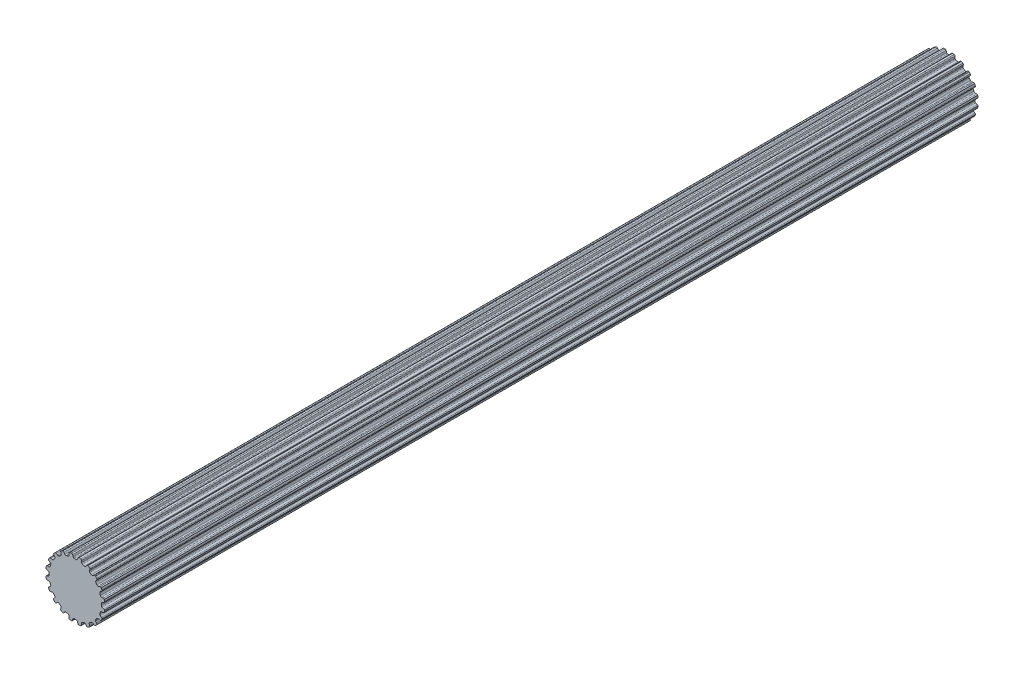
SolidWorks part; units mm, degrees
ref_plane "Front Plane" through (0, 0, 0) normal (0, 0, 1) x (1, 0, 0)
ref_plane "Top Plane" through (0, 0, 0) normal (0, 1, 0) x (1, 0, 0)
ref_plane "Right Plane" through (0, 0, 0) normal (1, 0, 0) x (0, 0, -1)
sketch "Sketch1" plane through (0, 0, 0) normal (0, 0, 1) x (1, 0, 0)
  line L0 (-0.1069, 2.9699) -> (0.1069, 2.9699)
  line L1 (0.3159, 3.2375) -> (0.2537, 3.0575)
  line L2 (-0.2964, 3.2367) -> (-0.2318, 3.0575)
  line L3 (-0.2964, 3.2367) -> (0.3159, 3.2375) construction
  line L4 (0, 3.3252) -> (0, 0) construction
  line L5 (-0.2318, 3.0575) -> (0.2537, 3.0575) construction
  line L6 (-0.4281, 3.3241) -> (0.4281, 3.3263) construction
  line L7 (0.7183, 3.1698) -> (0.7244, 2.9795)
  line L8 (0.816, 2.8576) -> (1.0195, 2.7915)
  line L9 (1.3009, 2.9815) -> (1.1862, 2.8295)
  line L10 (1.6627, 2.7927) -> (1.6097, 2.6099)
  line L11 (1.6591, 2.4655) -> (1.8322, 2.3398)
  line L12 (2.1585, 2.4335) -> (2.0025, 2.3245)
  line L13 (2.4443, 2.1423) -> (2.3374, 1.9847)
  line L14 (2.3398, 1.8322) -> (2.4655, 1.6591)
  line L15 (2.8049, 1.6474) -> (2.6228, 1.5919)
  line L16 (2.9866, 1.2821) -> (2.8363, 1.1653)
  line L17 (2.7915, 1.0195) -> (2.8576, 0.816)
  line L18 (3.1767, 0.7) -> (2.9863, 0.7035)
  line L19 (3.2367, 0.2964) -> (3.0575, 0.2318)
  line L20 (2.9699, 0.1069) -> (2.9699, -0.1069)
  line L21 (3.2375, -0.3159) -> (3.0575, -0.2537)
  line L22 (3.1698, -0.7183) -> (2.9795, -0.7244)
  line L23 (2.8576, -0.816) -> (2.7915, -1.0195)
  line L24 (2.9815, -1.3009) -> (2.8295, -1.1862)
  line L25 (2.7927, -1.6627) -> (2.6099, -1.6097)
  line L26 (2.4655, -1.6591) -> (2.3398, -1.8322)
  line L27 (2.4335, -2.1585) -> (2.3245, -2.0025)
  line L28 (2.1423, -2.4443) -> (1.9847, -2.3374)
  line L29 (1.8322, -2.3398) -> (1.6591, -2.4655)
  line L30 (1.6474, -2.8049) -> (1.5919, -2.6228)
  line L31 (1.2821, -2.9866) -> (1.1653, -2.8363)
  line L32 (1.0195, -2.7915) -> (0.816, -2.8576)
  line L33 (0.7, -3.1767) -> (0.7035, -2.9863)
  line L34 (0.2964, -3.2367) -> (0.2318, -3.0575)
  line L35 (0.1069, -2.9699) -> (-0.1069, -2.9699)
  line L36 (-0.3159, -3.2375) -> (-0.2537, -3.0575)
  line L37 (-0.7183, -3.1698) -> (-0.7244, -2.9795)
  line L38 (-0.816, -2.8576) -> (-1.0195, -2.7915)
  line L39 (-1.3009, -2.9815) -> (-1.1862, -2.8295)
  line L40 (-1.6627, -2.7927) -> (-1.6097, -2.6099)
  line L41 (-1.6591, -2.4655) -> (-1.8322, -2.3398)
  line L42 (-2.1585, -2.4335) -> (-2.0025, -2.3245)
  line L43 (-2.4443, -2.1423) -> (-2.3374, -1.9847)
  line L44 (-2.3398, -1.8322) -> (-2.4655, -1.6591)
  line L45 (-2.8049, -1.6474) -> (-2.6228, -1.5919)
  line L46 (-2.9866, -1.2821) -> (-2.8363, -1.1653)
  line L47 (-2.7915, -1.0195) -> (-2.8576, -0.816)
  line L48 (-3.1767, -0.7) -> (-2.9863, -0.7035)
  line L49 (-3.2367, -0.2964) -> (-3.0575, -0.2318)
  line L50 (-2.9699, -0.1069) -> (-2.9699, 0.1069)
  line L51 (-3.2375, 0.3159) -> (-3.0575, 0.2537)
  line L52 (-3.1698, 0.7183) -> (-2.9795, 0.7244)
  line L53 (-2.8576, 0.816) -> (-2.7915, 1.0195)
  line L54 (-2.9815, 1.3009) -> (-2.8295, 1.1862)
  line L55 (-2.7927, 1.6627) -> (-2.6099, 1.6097)
  line L56 (-2.4655, 1.6591) -> (-2.3398, 1.8322)
  line L57 (-2.4335, 2.1585) -> (-2.3245, 2.0025)
  line L58 (-2.1423, 2.4443) -> (-1.9847, 2.3374)
  line L59 (-1.8322, 2.3398) -> (-1.6591, 2.4655)
  line L60 (-1.6474, 2.8049) -> (-1.5919, 2.6228)
  line L61 (-1.2821, 2.9866) -> (-1.1653, 2.8363)
  line L62 (-1.0195, 2.7915) -> (-0.816, 2.8576)
  line L63 (-0.7, 3.1767) -> (-0.7035, 2.9863)
  line L64 (0.4281, 3.3263) -> (0.62, 3.2938)
  line L65 (1.4351, 3.0312) -> (1.6075, 2.9409)
  line L66 (2.3015, 2.4394) -> (2.4376, 2.3003)
  line L67 (2.9427, 1.6088) -> (3.0291, 1.4344)
  line L68 (3.2958, 0.6207) -> (3.3241, 0.4281)
  line L69 (3.3263, -0.4281) -> (3.2938, -0.62)
  line L70 (3.0312, -1.4351) -> (2.9409, -1.6075)
  line L71 (2.4394, -2.3015) -> (2.3003, -2.4376)
  line L72 (1.6088, -2.9427) -> (1.4344, -3.0291)
  line L73 (0.6207, -3.2958) -> (0.4281, -3.3241)
  line L74 (-0.4281, -3.3263) -> (-0.62, -3.2938)
  line L75 (-1.4351, -3.0312) -> (-1.6075, -2.9409)
  line L76 (-2.3015, -2.4394) -> (-2.4376, -2.3003)
  line L77 (-2.9427, -1.6088) -> (-3.0291, -1.4344)
  line L78 (-3.2958, -0.6207) -> (-3.3241, -0.4281)
  line L79 (-3.3263, 0.4281) -> (-3.2938, 0.62)
  line L80 (-3.0312, 1.4351) -> (-2.9409, 1.6075)
  line L81 (-2.4394, 2.3015) -> (-2.3003, 2.4376)
  line L82 (-1.6088, 2.9427) -> (-1.4344, 3.0291)
  line L83 (-0.6207, 3.2958) -> (-0.4281, 3.3241)
  arc A0 (0.2537, 3.0575) -> (0.1069, 2.9699) centre (0.1283, 3.1009) cw
  arc A1 (-0.2318, 3.0575) -> (-0.1069, 2.9699) centre (-0.1069, 3.1026) ccw
  arc A2 (0.62, 3.2938) -> (0.7183, 3.1698) centre (0.5856, 3.1656) cw
  arc A3 (0.7244, 2.9795) -> (0.816, 2.8576) centre (0.857, 2.9838) ccw
  arc A4 (-0.4281, 3.3241) -> (-0.2964, 3.2367) centre (-0.4213, 3.1916) cw
  arc A5 (0.4281, 3.3263) -> (0.3159, 3.2375) centre (0.4413, 3.1942) ccw
  arc A6 (1.1862, 2.8295) -> (1.0195, 2.7915) centre (1.0802, 2.9095) cw
  arc A7 (1.4351, 3.0312) -> (1.3009, 2.9815) centre (1.4068, 2.9015) ccw
  arc A8 (1.6075, 2.9409) -> (1.6627, 2.7927) centre (1.5352, 2.8297) cw
  arc A9 (1.6097, 2.6099) -> (1.6591, 2.4655) centre (1.7371, 2.5729) ccw
  arc A10 (2.0025, 2.3245) -> (1.8322, 2.3398) centre (1.9264, 2.4332) cw
  arc A11 (2.3015, 2.4394) -> (2.1585, 2.4335) centre (2.2346, 2.3248) ccw
  arc A12 (2.4376, 2.3003) -> (2.4443, 2.1423) centre (2.3345, 2.2168) cw
  arc A13 (2.3374, 1.9847) -> (2.3398, 1.8322) centre (2.4472, 1.9102) ccw
  arc A14 (2.6228, 1.5919) -> (2.4655, 1.6591) centre (2.5841, 1.7189) cw
  arc A15 (2.9427, 1.6088) -> (2.8049, 1.6474) centre (2.8436, 1.5205) ccw
  arc A16 (3.0291, 1.4344) -> (2.9866, 1.2821) centre (2.9052, 1.3869) cw
  arc A17 (2.8363, 1.1653) -> (2.7915, 1.0195) centre (2.9177, 1.0605) ccw
  arc A18 (2.9863, 0.7035) -> (2.8576, 0.816) centre (2.9887, 0.8362) cw
  arc A19 (3.2958, 0.6207) -> (3.1767, 0.7) centre (3.1743, 0.5673) ccw
  arc A20 (3.3241, 0.4281) -> (3.2367, 0.2964) centre (3.1916, 0.4213) cw
  arc A21 (3.0575, 0.2318) -> (2.9699, 0.1069) centre (3.1026, 0.1069) ccw
  arc A22 (3.0575, -0.2537) -> (2.9699, -0.1069) centre (3.1009, -0.1283) cw
  arc A23 (3.3263, -0.4281) -> (3.2375, -0.3159) centre (3.1942, -0.4413) ccw
  arc A24 (3.2938, -0.62) -> (3.1698, -0.7183) centre (3.1656, -0.5856) cw
  arc A25 (2.9795, -0.7244) -> (2.8576, -0.816) centre (2.9838, -0.857) ccw
  arc A26 (2.8295, -1.1862) -> (2.7915, -1.0195) centre (2.9095, -1.0802) cw
  arc A27 (3.0312, -1.4351) -> (2.9815, -1.3009) centre (2.9015, -1.4068) ccw
  arc A28 (2.9409, -1.6075) -> (2.7927, -1.6627) centre (2.8297, -1.5352) cw
  arc A29 (2.6099, -1.6097) -> (2.4655, -1.6591) centre (2.5729, -1.7371) ccw
  arc A30 (2.3245, -2.0025) -> (2.3398, -1.8322) centre (2.4332, -1.9264) cw
  arc A31 (2.4394, -2.3015) -> (2.4335, -2.1585) centre (2.3248, -2.2346) ccw
  arc A32 (2.3003, -2.4376) -> (2.1423, -2.4443) centre (2.2168, -2.3345) cw
  arc A33 (1.9847, -2.3374) -> (1.8322, -2.3398) centre (1.9102, -2.4472) ccw
  arc A34 (1.5919, -2.6228) -> (1.6591, -2.4655) centre (1.7189, -2.5841) cw
  arc A35 (1.6088, -2.9427) -> (1.6474, -2.8049) centre (1.5205, -2.8436) ccw
  arc A36 (1.4344, -3.0291) -> (1.2821, -2.9866) centre (1.3869, -2.9052) cw
  arc A37 (1.1653, -2.8363) -> (1.0195, -2.7915) centre (1.0605, -2.9177) ccw
  arc A38 (0.7035, -2.9863) -> (0.816, -2.8576) centre (0.8362, -2.9887) cw
  arc A39 (0.6207, -3.2958) -> (0.7, -3.1767) centre (0.5673, -3.1743) ccw
  arc A40 (0.4281, -3.3241) -> (0.2964, -3.2367) centre (0.4213, -3.1916) cw
  arc A41 (0.2318, -3.0575) -> (0.1069, -2.9699) centre (0.1069, -3.1026) ccw
  arc A42 (-0.2537, -3.0575) -> (-0.1069, -2.9699) centre (-0.1283, -3.1009) cw
  arc A43 (-0.4281, -3.3263) -> (-0.3159, -3.2375) centre (-0.4413, -3.1942) ccw
  arc A44 (-0.62, -3.2938) -> (-0.7183, -3.1698) centre (-0.5856, -3.1656) cw
  arc A45 (-0.7244, -2.9795) -> (-0.816, -2.8576) centre (-0.857, -2.9838) ccw
  arc A46 (-1.1862, -2.8295) -> (-1.0195, -2.7915) centre (-1.0802, -2.9095) cw
  arc A47 (-1.4351, -3.0312) -> (-1.3009, -2.9815) centre (-1.4068, -2.9015) ccw
  arc A48 (-1.6075, -2.9409) -> (-1.6627, -2.7927) centre (-1.5352, -2.8297) cw
  arc A49 (-1.6097, -2.6099) -> (-1.6591, -2.4655) centre (-1.7371, -2.5729) ccw
  arc A50 (-2.0025, -2.3245) -> (-1.8322, -2.3398) centre (-1.9264, -2.4332) cw
  arc A51 (-2.3015, -2.4394) -> (-2.1585, -2.4335) centre (-2.2346, -2.3248) ccw
  arc A52 (-2.4376, -2.3003) -> (-2.4443, -2.1423) centre (-2.3345, -2.2168) cw
  arc A53 (-2.3374, -1.9847) -> (-2.3398, -1.8322) centre (-2.4472, -1.9102) ccw
  arc A54 (-2.6228, -1.5919) -> (-2.4655, -1.6591) centre (-2.5841, -1.7189) cw
  arc A55 (-2.9427, -1.6088) -> (-2.8049, -1.6474) centre (-2.8436, -1.5205) ccw
  arc A56 (-3.0291, -1.4344) -> (-2.9866, -1.2821) centre (-2.9052, -1.3869) cw
  arc A57 (-2.8363, -1.1653) -> (-2.7915, -1.0195) centre (-2.9177, -1.0605) ccw
  arc A58 (-2.9863, -0.7035) -> (-2.8576, -0.816) centre (-2.9887, -0.8362) cw
  arc A59 (-3.2958, -0.6207) -> (-3.1767, -0.7) centre (-3.1743, -0.5673) ccw
  arc A60 (-3.3241, -0.4281) -> (-3.2367, -0.2964) centre (-3.1916, -0.4213) cw
  arc A61 (-3.0575, -0.2318) -> (-2.9699, -0.1069) centre (-3.1026, -0.1069) ccw
  arc A62 (-3.0575, 0.2537) -> (-2.9699, 0.1069) centre (-3.1009, 0.1283) cw
  arc A63 (-3.3263, 0.4281) -> (-3.2375, 0.3159) centre (-3.1942, 0.4413) ccw
  arc A64 (-3.2938, 0.62) -> (-3.1698, 0.7183) centre (-3.1656, 0.5856) cw
  arc A65 (-2.9795, 0.7244) -> (-2.8576, 0.816) centre (-2.9838, 0.857) ccw
  arc A66 (-2.8295, 1.1862) -> (-2.7915, 1.0195) centre (-2.9095, 1.0802) cw
  arc A67 (-3.0312, 1.4351) -> (-2.9815, 1.3009) centre (-2.9015, 1.4068) ccw
  arc A68 (-2.9409, 1.6075) -> (-2.7927, 1.6627) centre (-2.8297, 1.5352) cw
  arc A69 (-2.6099, 1.6097) -> (-2.4655, 1.6591) centre (-2.5729, 1.7371) ccw
  arc A70 (-2.3245, 2.0025) -> (-2.3398, 1.8322) centre (-2.4332, 1.9264) cw
  arc A71 (-2.4394, 2.3015) -> (-2.4335, 2.1585) centre (-2.3248, 2.2346) ccw
  arc A72 (-2.3003, 2.4376) -> (-2.1423, 2.4443) centre (-2.2168, 2.3345) cw
  arc A73 (-1.9847, 2.3374) -> (-1.8322, 2.3398) centre (-1.9102, 2.4472) ccw
  arc A74 (-1.5919, 2.6228) -> (-1.6591, 2.4655) centre (-1.7189, 2.5841) cw
  arc A75 (-1.6088, 2.9427) -> (-1.6474, 2.8049) centre (-1.5205, 2.8436) ccw
  arc A76 (-1.4344, 3.0291) -> (-1.2821, 2.9866) centre (-1.3869, 2.9052) cw
  arc A77 (-1.1653, 2.8363) -> (-1.0195, 2.7915) centre (-1.0605, 2.9177) ccw
  arc A78 (-0.7035, 2.9863) -> (-0.816, 2.8576) centre (-0.8362, 2.9887) cw
  arc A79 (-0.6207, 3.2958) -> (-0.7, 3.1767) centre (-0.5673, 3.1743) ccw
  point P14 (0, 2.9699)
  point P247 (0, 0)
  dimension "D4" = 0.1327
  dimension "D8" = 20
  dimension "D1" = 2.9699
  dimension "D2" = 0.2139
  dimension "D3" = 0.1904
  dimension "D5" = 0.0877
  dimension "D6" = 0.4855
  dimension "D7" = 0.8563
extrude "Boss-Extrude1" add sketch "Sketch1" along normal mid plane 99.314
sketch "Sketch2" plane through (0, 0, 49.657) normal (0, 0, 1) x (1, 0, 0)
  circle A0 centre (0, 0) radius 3.3516 construction
sketch "Sketch3" plane through (0, 0, -49.657) normal (0, 0, -1) x (-1, 0, 0)
  circle A0 centre (0, 0) radius 3.3516 construction
  circle A1 centre (0, 0) radius 3.3516 construction
sketch "Sketch4" plane through (0, 0, 0) normal (1, 0, 0) x (0, 0, -1)
  line L0 (49.657, 0) -> (-49.657, 0) construction
  line L2 (0, 9.7112) -> (0, -9.7112) construction
  point P6 (0, 0)
sketch "Sketch6" plane through (0, 0, 0) normal (0, 1, 0) x (1, 0, 0)
  line L0 (13.3396, 0) -> (-13.3396, 0) construction
  line L1 (0, 49.657) -> (0, -49.657) construction
